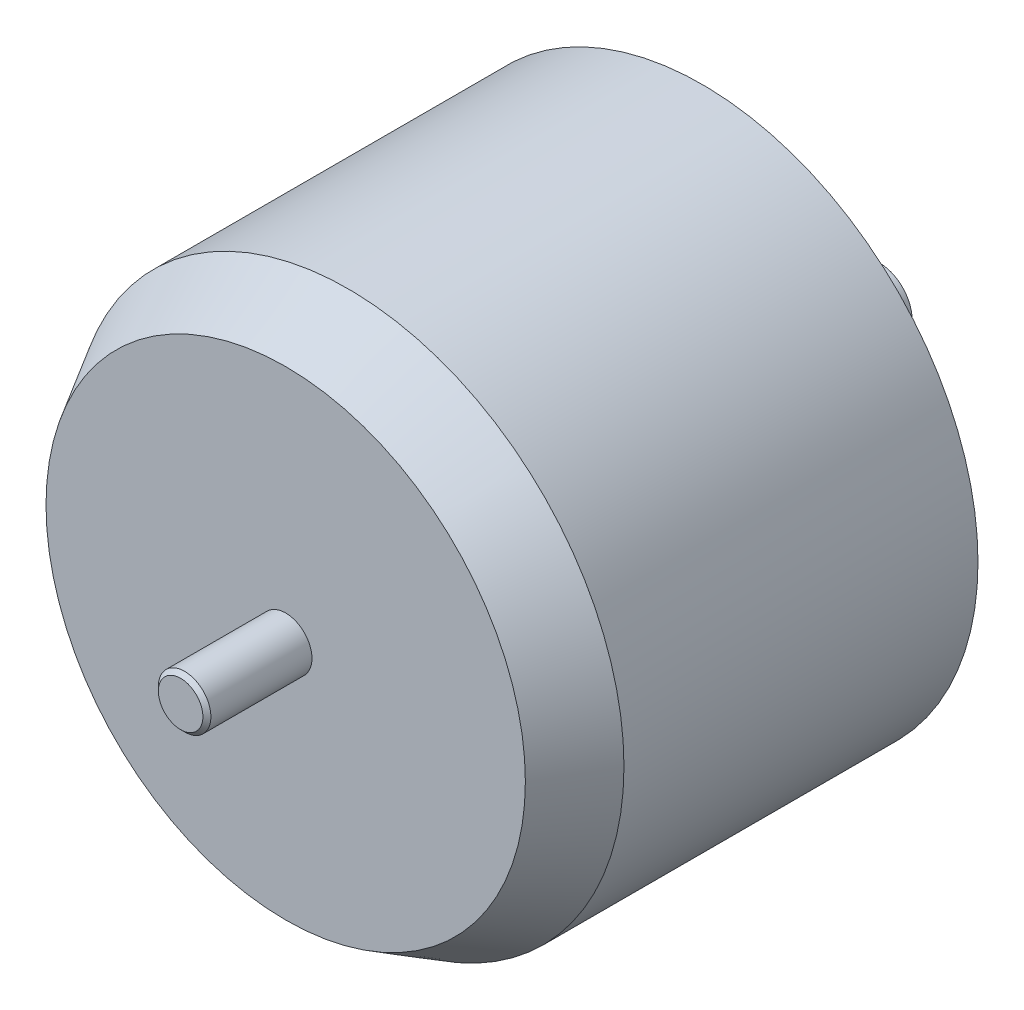
SolidWorks part; units mm, degrees
ref_plane "Front" through (0, 0, 0) normal (0, 0, 1) x (1, 0, 0)
ref_plane "Top" through (0, 0, 0) normal (0, 1, 0) x (1, 0, 0)
ref_plane "Right" through (0, 0, 0) normal (1, 0, 0) x (0, 0, -1)
sketch "Sketch1" plane through (0, 0, 0) normal (0, 1, 0) x (1, 0, 0)
  line L0 (1.25, 1.9) -> (0, 1.9)
  line L1 (0, 1.9) -> (0, -22.7)
  line L2 (0, -22.7) -> (0.8476, -22.7)
  line L3 (0.8476, -22.7) -> (1, -22.5476)
  line L4 (1, -22.5476) -> (1, -18.7)
  line L5 (1, -18.7) -> (9.1259, -18.7)
  line L6 (9.1259, -18.7) -> (10.5, -16.32)
  line L7 (10.5, -16.32) -> (10.5, -2.8406)
  line L8 (10.5, -2.8406) -> (5.58, 0)
  line L9 (5.58, 0) -> (2.75, 0)
  line L10 (2.75, 0) -> (2.75, 0.95)
  line L11 (2.75, 0.95) -> (1.25, 0.95)
  line L12 (1.25, 0.95) -> (1.25, 1.9)
  line L13 (0, 1.9) -> (0, -22.7) construction
revolve "Revolve1" add sketch "Sketch1" angle 360 about L13
sketch "Sketch2" plane through (0, 0, -1.9) normal (0, 0, -1) x (-1, 0, 0)
  circle A1 centre (0, 0) radius 1.25
  circle A2 centre (0, 0) radius 1.25
  dimension "D1" = 0
extrude "Boss-Extrude1" add sketch "Sketch2" along normal blind 2
